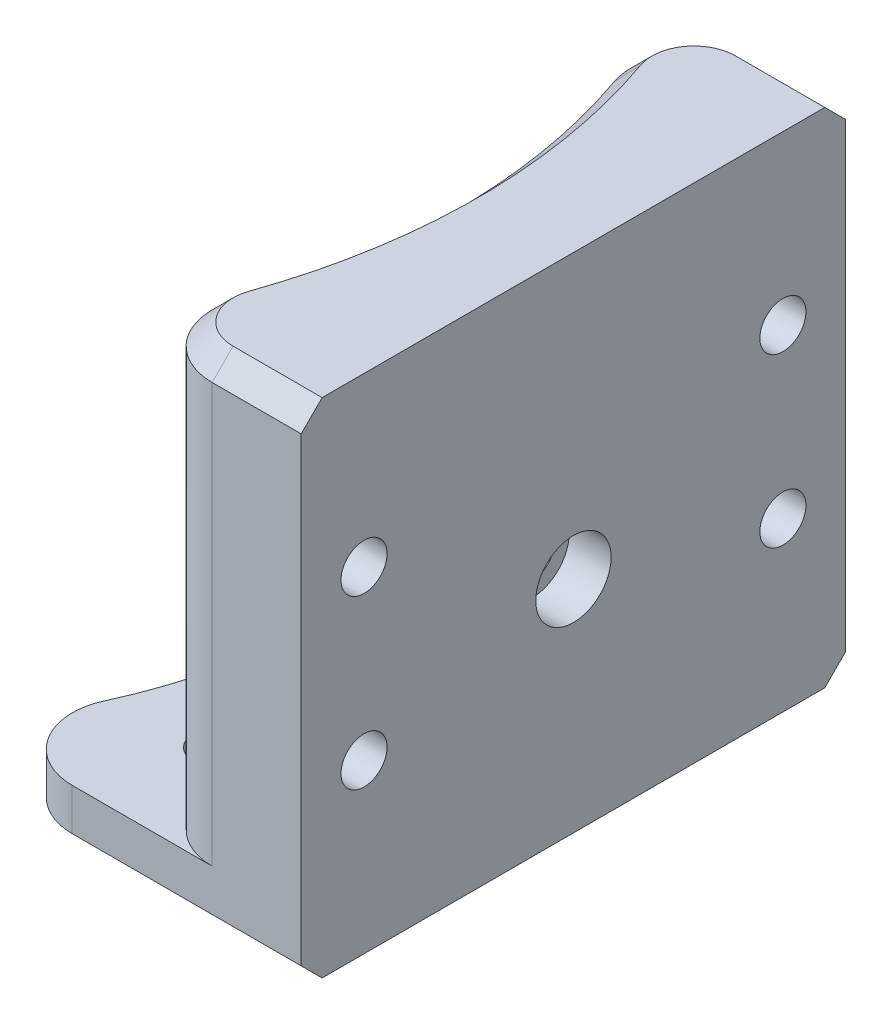
SolidWorks part; units mm, degrees
ref_plane "Спереди" through (0, 0, 0) normal (0, 0, 1) x (1, 0, 0)
ref_plane "Сверху" through (0, 0, 0) normal (0, 1, 0) x (1, 0, 0)
ref_plane "Справа" through (0, 0, 0) normal (1, 0, 0) x (0, 0, -1)
sketch "Эскиз1" plane through (0, 0, 0) normal (0, 1, 0) x (1, 0, 0)
  line L0 (23.6854, 8) -> (23.6854, -8) construction
  line L1 (16.4924, 13) -> (32.75, 13)
  line L2 (16.4924, 13) -> (16.4924, -13) construction
  line L3 (16.4924, -13) -> (32.75, -13)
  line L4 (32.75, 13) -> (32.75, -13)
  circle A0 centre (0, 0) radius 25 construction
  circle A2 centre (0, 0) radius 21
  circle A3 centre (23.6854, 8) radius 1.1
  circle A4 centre (23.6854, -8) radius 1.1
  dimension "D1" = 50
  dimension "D6" = 2.2
  dimension "D7" = 2.2
  dimension "D2" = 4
  dimension "D3" = 26
  dimension "D4" = 32.75
  dimension "D5" = 16
extrude "Бобышка-Вытянуть1" add sketch "Эскиз1" along normal blind 24 contours A2 L3 L4 L1 A4 A3
sketch "Эскиз2" plane through (0, 24, 0) normal (0, 1, 0) x (1, 0, 0)
  circle A0 centre (0, 0) radius 25 construction
  circle A1 centre (0, 0) radius 27.2
  dimension "D1" = 2.2
extrude "Вырез-Вытянуть1" cut sketch "Эскиз2" against normal offset from surface (21 mm away) 3 up to face at (23.6854, 0, 9.1)
fillet "Скругление1" radius 3 4 edges at (23.8923, 13.5, 13) (23.8923, 13.5, -13) (16.4924, 1.5, -13) (16.4924, 1.5, 13)
sketch "Эскиз3" plane through (32.75, 0, 0) normal (1, 0, 0) x (0, 0, -1)
  line L0 (13, 0) -> (-13, 0) construction
  line L1 (-13, 12) -> (13, 12) construction
  line L2 (-10, 16) -> (-10, 8) construction
  line L3 (0, 0) -> (0, 24) construction
  line L4 (13, 24) -> (-13, 24) construction
  line L5 (-13, 24) -> (-13, 0) construction
  line L6 (13, 24) -> (13, 0) construction
  circle A0 centre (0, 10.5) radius 1.1
  circle A2 centre (-10, 16) radius 1.1
  circle A3 centre (-10, 8) radius 1.1
  circle A4 centre (10, 8) radius 1.1
  circle A5 centre (10, 16) radius 1.1
  point P4 (0, 0)
  point P17 (-13, 12)
  dimension "D1" = 2.2
  dimension "D3" = 2.2
  dimension "D2" = 10.5
  dimension "D4" = 8
  dimension "D5" = 20
extrude "Вырез-Вытянуть2" cut sketch "Эскиз3" against normal through all
chamfer "Фаска2" distance 1 angle 45 10 edges at (30.6232, 24, -13) (26.0489, 24, -11.7349) (27.2, 24, 0) (30.6232, 24, 13) (26.0489, 24, 11.7349) (27.2837, 0, -13) (19.2925, 0, -11.6202) (21, 0, 0) (19.2925, 0, 11.6202) (27.2837, 0, 13)
sketch "Эскиз4" plane through (0, 0, 0) normal (1, 0, 0) x (0, 0, -1)
  line L0 (-13, 12) -> (13, 12) construction
  line L1 (-8, 14.8453) -> (-8, 17.1547)
  line L2 (-8, 17.1547) -> (-10, 18.3094)
  line L3 (-10, 18.3094) -> (-12, 17.1547)
  line L4 (-12, 17.1547) -> (-12, 14.8453)
  line L5 (-12, 14.8453) -> (-10, 13.6906)
  line L6 (-10, 13.6906) -> (-8, 14.8453)
  line L7 (-13, 23) -> (-13, 1) construction
  line L8 (13, 23) -> (13, 1) construction
  line L9 (0, 24) -> (0, 0) construction
  line L10 (12, 24) -> (-12, 24) construction
  line L11 (12, 0) -> (-12, 0) construction
  line L12 (-10, 10.3094) -> (-8, 9.1547)
  line L13 (-12, 9.1547) -> (-10, 10.3094)
  line L14 (-12, 6.8453) -> (-12, 9.1547)
  line L15 (-10, 5.6906) -> (-12, 6.8453)
  line L16 (-8, 6.8453) -> (-10, 5.6906)
  line L17 (-8, 9.1547) -> (-8, 6.8453)
  line L18 (8, 9.1547) -> (8, 6.8453)
  line L19 (8, 6.8453) -> (10, 5.6906)
  line L20 (10, 5.6906) -> (12, 6.8453)
  line L21 (12, 6.8453) -> (12, 9.1547)
  line L22 (12, 9.1547) -> (10, 10.3094)
  line L23 (10, 10.3094) -> (8, 9.1547)
  line L24 (10, 13.6906) -> (8, 14.8453)
  line L25 (12, 14.8453) -> (10, 13.6906)
  line L26 (12, 17.1547) -> (12, 14.8453)
  line L27 (10, 18.3094) -> (12, 17.1547)
  line L28 (8, 17.1547) -> (10, 18.3094)
  line L29 (8, 14.8453) -> (8, 17.1547)
  circle A0 centre (-10, 16) radius 2 construction
  dimension "D1" = 4
extrude "Вырез-Вытянуть3" cut sketch "Эскиз4" along normal offset from surface (28.75 mm away) 4 up to face at (32.75, 16, -8.9)
sketch "Эскиз5" plane through (32.75, 0, 0) normal (1, 0, 0) x (0, 0, -1)
  circle A0 centre (0, 10.5) radius 1.8
  dimension "D1" = 3.6
extrude "Вырез-Вытянуть4" cut sketch "Эскиз5" against normal blind 2
sketch "Эскиз6" plane through (0, 0, 0) normal (0, -1, 0) x (1, 0, 0)
  circle A0 centre (23.6854, 8) radius 1.8
  circle A1 centre (23.6854, -8) radius 1.8
  dimension "D1" = 3.6
  dimension "D2" = 3.6
extrude "Вырез-Вытянуть5" cut sketch "Эскиз6" against normal blind 1
equation "\"motor_diameter\"= 30"
equation "\"mm_diameter\"= IIF ( \"motor_diameter\" < 34 , 41 , \"motor_diameter\" + 8 )"
equation "\"upper_shafts_diameter\"= 5"
equation "\"upper_shats_length\"= 180"
equation "\"upper_bearing_d1\"= 10"
equation "\"upper_bearing_d2\"= 5"
equation "\"upper_bearing_h\"= 15"
equation "\"lower_shafts_diameter\"= 5"
equation "\"lower_shafts_length\"= 180"
equation "\"lower_bearing_d1\"= 10"
equation "\"lower_bearing_d2\"= 5"
equation "\"lower_bearing_h\"= 15"
equation "\"print_offset\"= 0.2"
equation "\"bh_screws_d\"= 2"
equation "\"bh_screws_h\"= 20"
equation "\"bh_screws_hh_d\"= 3.4"
equation "\"bh_screws_hh_h\"= 2"
equation "\"bh_nut_d\"= 3.8"
equation "\"bh_nut_h\"= 2"
equation "\"motor_screws_d\"= 3"
equation "\"motor_screws_h\"= 16"
equation "\"motor_screws_hh_d\"= 5.5"
equation "\"motor_screws_hh_h\"= 3"
equation "\"plate_hole_distance\"= 25.4"
equation "\"plate_screws_d\"= 6.5"
equation "\"shafts_diameter\"= IIF ( \"mm_diameter\" < 42 , 42 + 8 , \"mm_diameter\" + 8 )"
equation "\"central_hole_diameter\"= 8"
equation "\"bh_thikness\"= 4"
equation "\"ends_screws_d\"= 4"
equation "\"ends_screws_h\"= 16"
equation "\"ends_screws_hh_d\"= 6.7"
equation "\"ends_screws_hh_h\"= 4.1"
equation "\"ends_nut_d\"= 6.8"
equation "\"ends_nut_h\"= 3"
equation "\"system_radius\" = ( \"shafts_diameter\" + 12 + \"bh_thikness\" / 2 ) / 2"
equation "\"encoder_distance\"= \"system_radius\" + 4"
equation "\"tape_position\"= \"encoder_distance\" - 2 + 3.9 + 1.7 / 2"
equation "\"D1@Эскиз1\"=\"shafts_diameter\""
equation "\"D2@Эскиз1\"=\"bh_thikness\""
equation "\"D4@Эскиз1\"=\"tape_position\"-6"
equation "\"D6@Эскиз1\"=\"bh_screws_d\"+\"print_offset\""
equation "\"D7@Эскиз1\"=\"D6@Эскиз1\""
equation "\"D1@Бобышка-Вытянуть1\"=\"upper_bearing_h\"+6+3"
equation "\"D1@Эскиз2\"=\"bh_thikness\"/2+\"print_offset\""
equation "\"D1@Эскиз3\"=\"bh_screws_d\"+\"print_offset\""
equation "\"D2@Эскиз3\"=\"upper_bearing_h\"/2+3"
equation "\"D3@Эскиз3\"=\"bh_screws_d\"+\"print_offset\""
equation "\"D1@Эскиз4\"=\"bh_nut_d\"+\"print_offset\""
equation "\"D1@Вырез-Вытянуть3\"=12-8"
equation "\"D1@Эскиз5\"=\"bh_screws_hh_d\"+\"print_offset\""
equation "\"D1@Вырез-Вытянуть4\"=\"bh_screws_hh_h\""
equation "\"D1@Эскиз6\"=\"bh_screws_hh_d\"+\"print_offset\""
equation "\"D2@Эскиз6\"=\"D1@Эскиз6\""
